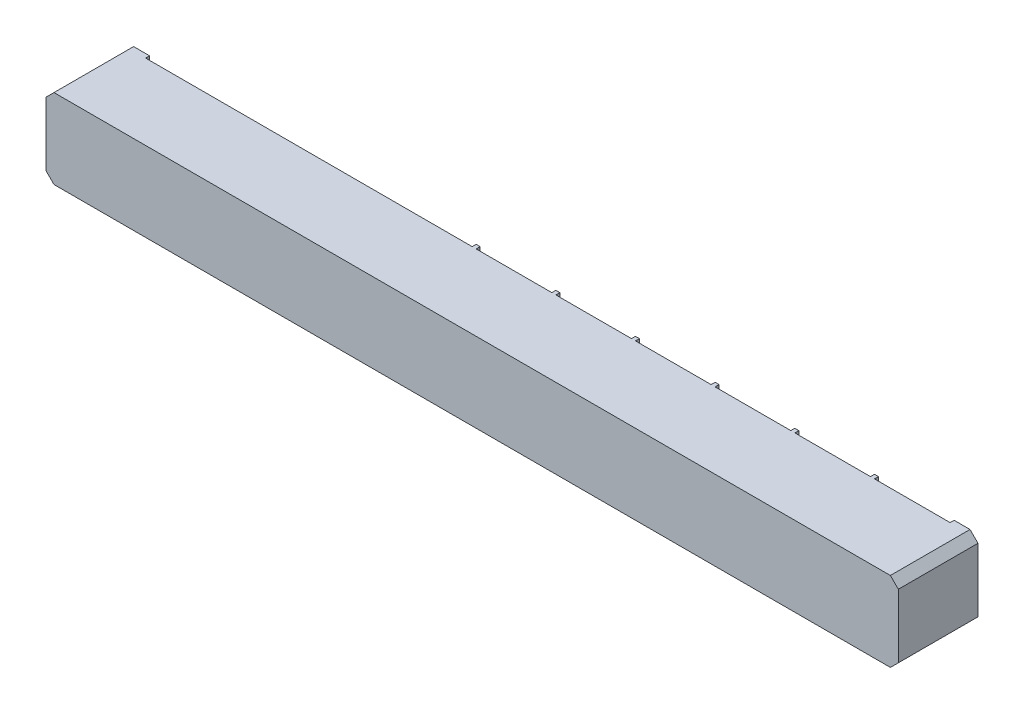
SolidWorks part; units mm, degrees
material "Polietileno reticulado"
ref_plane "Alzado" through (0, 0, 0) normal (0, 0, 1) x (1, 0, 0)
ref_plane "Planta" through (0, 0, 0) normal (0, 1, 0) x (1, 0, 0)
ref_plane "Vista lateral" through (0, 0, 0) normal (1, 0, 0) x (0, 0, -1)
sketch "Croquis1" plane through (0, 0, 0) normal (0, 0, 1) x (1, 0, 0)
  line L0 (-106.3083, -37.8713) -> (-126.3083, -37.8713)
  line L5 (-106.3083, 62.1287) -> (893.6917, 62.1287)
  line L6 (-106.3083, 62.1287) -> (-106.3083, -37.8713) construction
  line L7 (-106.3083, -37.8713) -> (893.6917, -37.8713)
  line L8 (893.6917, 62.1287) -> (893.6917, -37.8713) construction
  line L9 (293.6917, 62.1287) -> (293.6917, -37.8713)
  line L10 (393.6917, 62.1287) -> (393.6917, -37.8713)
  line L11 (493.6917, 62.1287) -> (493.6917, -37.8713)
  line L12 (593.6917, 62.1287) -> (593.6917, -37.8713)
  line L13 (693.6917, 62.1287) -> (693.6917, -37.8713)
  line L14 (793.6917, 62.1287) -> (793.6917, -37.8713)
  line L15 (-136.3083, -27.8713) -> (-136.3083, 52.1287)
  line L16 (-126.3083, 62.1287) -> (-106.3083, 62.1287)
  line L17 (-126.3083, -37.8713) -> (-136.3083, -27.8713)
  line L18 (-136.3083, 52.1287) -> (-126.3083, 62.1287)
  line L19 (893.6917, -37.8713) -> (923.6917, -37.8713)
  line L20 (933.6917, -27.8713) -> (933.6917, 52.1287)
  line L21 (923.6917, 62.1287) -> (893.6917, 62.1287)
  line L22 (923.6917, -37.8713) -> (933.6917, -27.8713)
  line L23 (933.6917, 52.1287) -> (923.6917, 62.1287)
  point P4 (-136.3083, 62.1287)
  point P5 (-136.3083, -37.8713)
  point P24 (933.6917, -37.8713)
  point P25 (933.6917, 62.1287)
  dimension "D1" = 1000
  dimension "D2" = 100
  dimension "D3" = 100
  dimension "D4" = 100
  dimension "D5" = 100
  dimension "D6" = 100
  dimension "D7" = 100
  dimension "D8" = 30
  dimension "100" = 100
  dimension "D9" = 30
extrude "Saliente-Extruir2" add sketch "Croquis1" along normal blind 100 contours L20 L23 L21 L5 L14 L7 L19 L22 | L14 L5 L13 L7 | L13 L5 L12 L7 | L12 L5 L11 L7 | L11 L5 L10 L7 | L10 L5 L9 L7 | L18 L15 L17 L0 L7 L9 L5 L16
sketch "Croquis2" plane through (0, 0, 0) normal (0, 0, 1) x (1, 0, 0)
  line L5 (-126.3083, 62.1287) -> (-126.3083, -37.8713) construction
  line L6 (-106.3083, 62.1287) -> (-106.3083, -37.8713)
  line L7 (303.6917, 62.1287) -> (303.6917, -37.8713)
  line L8 (923.6917, 62.1287) -> (-126.3083, 62.1287) construction
  line L9 (-126.3083, -37.8713) -> (923.6917, -37.8713) construction
  line L10 (903.6917, 62.1287) -> (903.6917, -37.8713)
  line L11 (808.6917, 62.1287) -> (808.6917, -37.8713)
  line L12 (803.6917, 62.1287) -> (803.6917, -37.8713)
  line L13 (708.6917, 62.1287) -> (708.6917, -37.8713)
  line L14 (703.6917, 62.1287) -> (703.6917, -37.8713)
  line L15 (608.6917, -37.8713) -> (608.6917, 62.1287)
  line L16 (603.6917, 62.1287) -> (603.6917, -37.8713)
  line L17 (903.6917, 62.1287) -> (808.6917, 62.1287)
  line L18 (903.6917, -37.8713) -> (808.6917, -37.8713)
  line L19 (803.6917, 62.1287) -> (708.6917, 62.1287)
  line L20 (803.6917, -37.8713) -> (708.6917, -37.8713)
  line L21 (703.6917, 62.1287) -> (608.6917, 62.1287)
  line L22 (703.6917, -37.8713) -> (608.6917, -37.8713)
  line L23 (508.6917, 62.1287) -> (508.6917, -37.8713)
  line L24 (503.6917, 62.1287) -> (503.6917, -37.8713)
  line L25 (603.6917, 62.1287) -> (508.6917, 62.1287)
  line L26 (603.6917, -37.8713) -> (508.6917, -37.8713)
  line L27 (408.6917, 62.1287) -> (408.6917, -37.8713)
  line L28 (403.6917, 62.1287) -> (403.6917, -37.8713)
  line L29 (308.6917, 62.1287) -> (308.6917, -37.8713)
  line L30 (-106.3083, 62.1287) -> (303.6917, 62.1287)
  line L31 (-106.3083, -37.8713) -> (303.6917, -37.8713)
  line L32 (308.6917, 62.1287) -> (403.6917, 62.1287)
  line L33 (308.6917, -37.8713) -> (403.6917, -37.8713)
  line L34 (408.6917, 62.1287) -> (503.6917, 62.1287)
  line L35 (408.6917, -37.8713) -> (503.6917, -37.8713)
  dimension "D3" = 20
  dimension "D4" = 5
  dimension "D5" = 20
  dimension "D6" = 95
  dimension "D7" = 5
  dimension "D8" = 95
  dimension "D9" = 5
  dimension "D10" = 95
  dimension "D11" = 5
  dimension "D12" = 95
  dimension "D13" = 5
  dimension "D14" = 95
  dimension "D15" = 5
  dimension "D16" = 95
extrude "Cortar-Extruir2" cut sketch "Croquis2" along normal blind 5
sketch "Croquis3" plane through (0, 0, 0) normal (0, 1, 0) x (1, 0, 0)
  line L0 (803.6917, -5) -> (803.6917, -100) construction
  line L2 (-126.3083, -100) -> (923.6917, -100) construction
  line L3 (808.6917, -5) -> (808.6917, -100) construction
  line L4 (903.6917, -5) -> (903.6917, -100) construction
  line L5 (808.6917, -5) -> (903.6917, -100) construction
  line L6 (903.6917, -5) -> (808.6917, -100) construction
  line L7 (803.6917, -100) -> (708.6917, -5) construction
  line L8 (708.6917, -5) -> (708.6917, -100) construction
  line L9 (708.6917, -100) -> (803.6917, -5) construction
  line L10 (608.6917, -5) -> (608.6917, -100) construction
  line L11 (508.6917, -5) -> (508.6917, -100) construction
  line L12 (408.6917, -5) -> (408.6917, -100) construction
  line L13 (303.6917, -5) -> (303.6917, -100) construction
  line L14 (303.6917, -100) -> (-106.3083, -5) construction
  line L15 (-106.3083, -5) -> (-106.3083, -100) construction
  line L16 (-106.3083, -100) -> (303.6917, -5) construction
  circle A0 centre (856.1917, -52.5) radius 15
  circle A1 centre (756.1917, -52.5) radius 15
  circle A2 centre (661.1917, -52.5) radius 15
  circle A3 centre (556.1917, -52.5) radius 15
  circle A4 centre (461.1917, -52.5) radius 15
  circle A5 centre (356.1917, -52.5) radius 15
  circle A6 centre (98.6917, -52.5) radius 35
  point P43 (98.6917, -52.5)
  dimension "D1" = 30
  dimension "D2" = 30
  dimension "D3" = 70
extrude "Saliente-Extruir3" add sketch "Croquis3" against normal blind 50 contours A0 | A1 | A2 | A3 | A4 | A5 | A6
